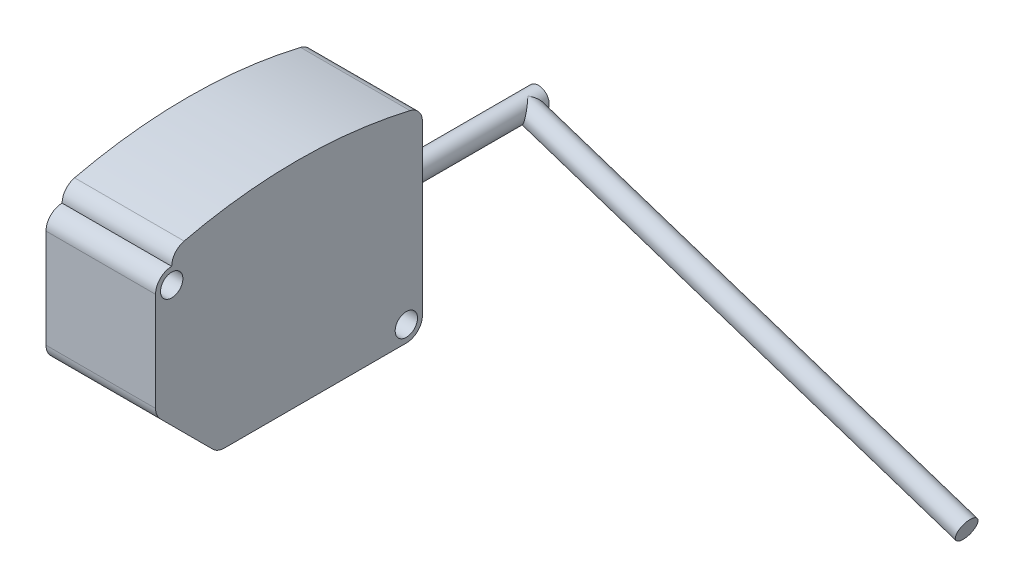
SolidWorks part; units mm, degrees
material "ABS"
ref_plane "Plan de face" through (0, 0, 0) normal (0, 0, 1) x (1, 0, 0)
ref_plane "Plan de dessus" through (0, 0, 0) normal (0, 1, 0) x (1, 0, 0)
ref_plane "Plan de droite" through (0, 0, 0) normal (1, 0, 0) x (0, 0, -1)
sketch "Esquisse2" plane through (0, 0, 0) normal (1, 0, 0) x (0, 0, -1)
  line L0 (-67.523, 1.523) -> (-84.477, 18.477)
  line L1 (-64.6275, 68.5) -> (-0.6671, 68.5) construction
  line L2 (0, 59.2) -> (0, 5.2)
  line L3 (-80.8, 59.2) -> (-85.7801, 59.2) construction
  line L5 (-80.8, 61.0346) -> (-80.8, 59.2) construction
  line L6 (-5.2, 0) -> (-63.8461, 0)
  line L7 (-86, 22.1539) -> (-86, 54)
  arc A0 (-4.0049, 64.2608) -> (-76.7951, 64.2608) centre (-40.4, -89.8524) ccw
  arc A1 (-76.7951, 64.2608) -> (-80.8, 59.2) centre (-75.6, 59.2) ccw
  arc A2 (-80.8, 59.2) -> (-86, 54) centre (-80.8, 54) ccw
  arc A3 (0, 5.2) -> (-5.2, 0) centre (-5.2, 5.2) cw
  arc A4 (-4.0049, 64.2608) -> (0, 59.2) centre (-5.2, 59.2) cw
  arc A5 (-67.523, 1.523) -> (-63.8461, 0) centre (-63.8461, 5.2) ccw
  arc A6 (-84.477, 18.477) -> (-86, 22.1539) centre (-80.8, 22.1539) cw
  circle A7 centre (-80.8, 54) radius 2.25
  circle A8 centre (-5.2, 5.2) radius 2.25
  point P9 (-86, 0)
  point P18 (-66, 0)
  point P21 (-86, 20)
  dimension "D3" = 48.8
  dimension "D2" = 75.6
  dimension "D6" = 4.5
  dimension "D1" = 86
  dimension "D4" = 68.5
  dimension "D5" = 20
extrude "Extrusion1" add sketch "Esquisse2" along normal mid plane 35.3
sketch "Esquisse3" plane through (17.65, 0, 0) normal (1, 0, 0) x (0, 0, -1)
  circle A0 centre (-80.8, 54) radius 3.6
  circle A1 centre (-5.2, 5.2) radius 3.6
  dimension "D1" = 7.2
extrude "Extrusion2" cut sketch "Esquisse3" against normal blind 6
mirror "Symétrie1" about plane through (0, 0, 0) normal (1, 0, 0) of "Extrusion2"
sketch "Esquisse4" plane through (0, 0, 0) normal (0, 0, -1) x (-1, 0, 0)
  circle A0 centre (0, 29.5) radius 3.5
  arc A1 (-12.2971, 11.8639) -> (-20.3738, 36.3671) centre (0, 29.5) ccw construction
  dimension "D1" = 7
extrude "Extrusion3" add sketch "Esquisse4" along normal blind 55
sketch "Esquisse6" plane through (-8.7708, 2.891, 0) normal (0.9497, -0.3131, 0) x (0, 0, -1)
  line L0 (27.1136, 28.0172) -> (50.5155, 28.0172) construction
  line L1 (55, 31.5172) -> (0, 31.5172) construction
  line L2 (0, 24.5172) -> (55, 24.5172) construction
  circle A0 centre (50.5155, 28.0172) radius 3.5
  dimension "D1" = 7
extrude "Extrusion4" add sketch "Esquisse6" along normal blind 150
